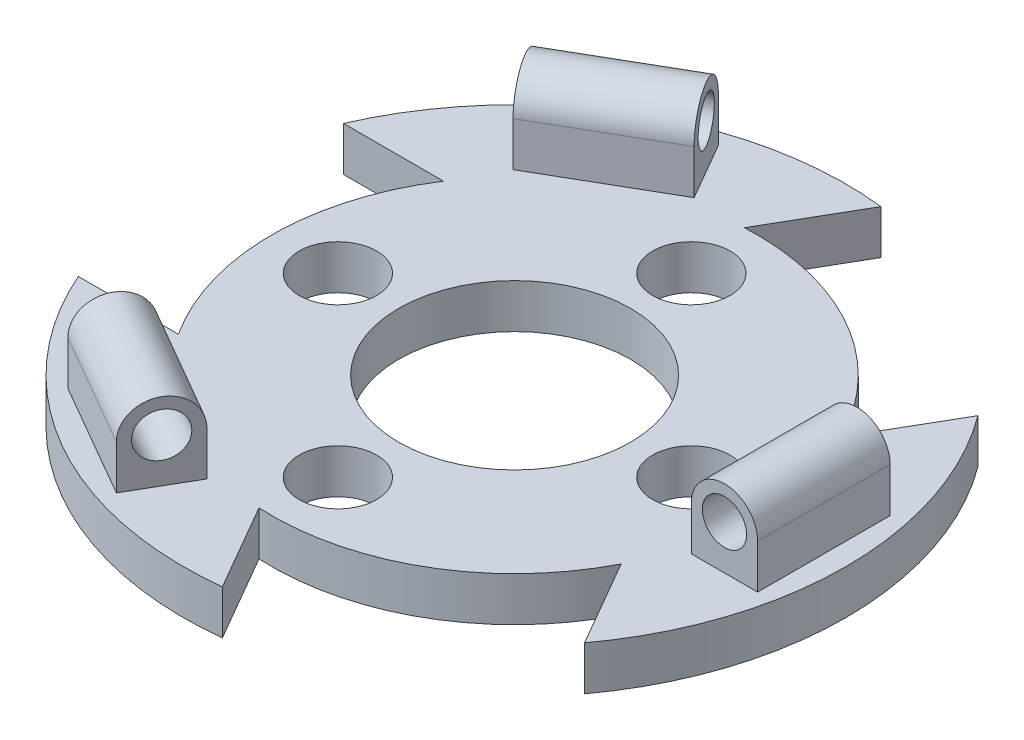
SolidWorks part; units mm, degrees
material "6061 Alloy"
ref_plane "Front Plane" through (0, 0, 0) normal (0, 0, 1) x (1, 0, 0)
ref_plane "Top Plane" through (0, 0, 0) normal (0, 1, 0) x (1, 0, 0)
ref_plane "Right Plane" through (0, 0, 0) normal (1, 0, 0) x (0, 0, -1)
sketch "Sketch1" plane through (0, 0, 0) normal (0, 1, 0) x (1, 0, 0)
  circle A0 centre (0, 0) radius 15
  circle A1 centre (0, 0) radius 5.25
  circle A2 centre (0, 8) radius 1.75
  circle A3 centre (0, 0) radius 8 construction
  circle A4 centre (8, 0) radius 1.75
  circle A5 centre (0, -8) radius 1.75
  circle A6 centre (-8, 0) radius 1.75
  dimension "D1" = 30
  dimension "D2" = 10.5
  dimension "D3" = 3.5
  dimension "D4" = 16
  dimension "D5" = 4
extrude "Boss-Extrude1" add sketch "Sketch1" along normal blind 2
sketch "Sketch2" plane through (0, 0, 0) normal (0, 0, 1) x (1, 0, 0)
  line L0 (11, 2) -> (11, 4)
  line L1 (15, 2) -> (-15, 2) construction
  line L2 (14, 4) -> (14, 2)
  line L3 (14, 2) -> (11, 2)
  line L4 (15, 0) -> (15, 2) construction
  arc A0 (14, 4) -> (11, 4) centre (12.5, 4) ccw
  circle A1 centre (12.5, 4) radius 1
  dimension "D1" = 1.5
  dimension "D2" = 2
  dimension "D3" = 1
  dimension "D4" = 2
extrude "Boss-Extrude2" add sketch "Sketch2" along normal mid plane 6
pattern_circular "CirPattern1" count 3 over 360 about axis through (0, 0, 0) along (0, 1, 0) of "Boss-Extrude2"
sketch "Sketch3" plane through (0, 2, 0) normal (0, 1, 0) x (1, 0, 0)
  line L0 (1.6777, -14.9059) -> (-0.5864, -10.9844)
  line L1 (12.07, -8.9059) -> (9.8059, -4.9844)
  line L2 (0, 0) -> (17.7911, -30.8151) construction
  line L3 (0, 0) -> (0, 24.587) construction
  line L4 (-13.7477, 6) -> (-9.2195, 6)
  line L5 (-13.7477, -6) -> (-9.2195, -6)
  line L6 (12.07, 8.9059) -> (9.8059, 4.9844)
  line L7 (1.6777, 14.9059) -> (-0.5864, 10.9844)
  arc A0 (9.8059, 4.9844) -> (-0.5864, 10.9844) centre (0, 0) ccw
  arc A1 (12.07, -8.9059) -> (12.07, 8.9059) centre (0, 0) ccw
  arc A2 (-13.7477, -6) -> (1.6777, -14.9059) centre (0, 0) ccw
  arc A3 (1.6777, 14.9059) -> (-13.7477, 6) centre (0, 0) ccw
  arc A4 (-0.5864, -10.9844) -> (9.8059, -4.9844) centre (0, 0) ccw
  arc A5 (-9.2195, 6) -> (-9.2195, -6) centre (0, 0) ccw
  dimension "D1" = 30
  dimension "D2" = 22
  dimension "D3" = 150
  dimension "D4" = 12
  dimension "D5" = 3
extrude "Cut-Extrude1" cut sketch "Sketch3" against normal blind 10 flip side to cut
